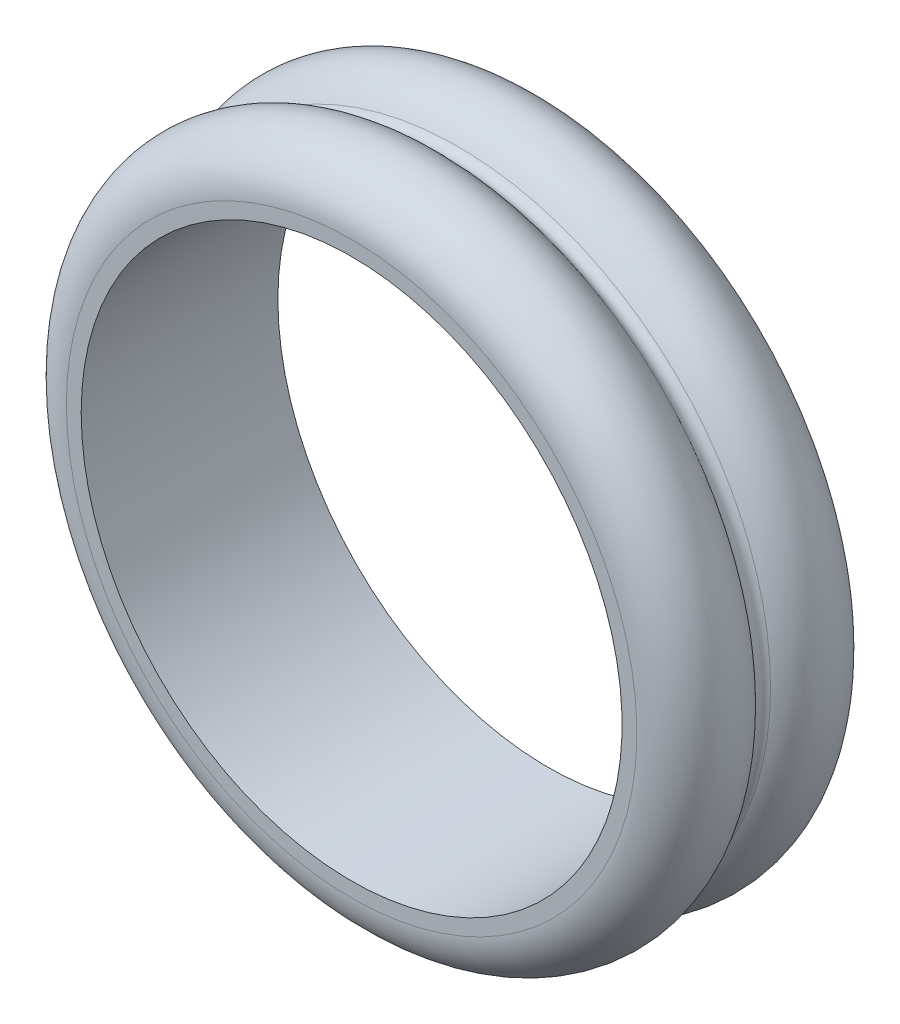
SolidWorks part; units mm, degrees
material "尼龙 6/10"
ref_plane "前视基准面" through (0, 0, 0) normal (0, 0, 1) x (1, 0, 0)
ref_plane "上视基准面" through (0, 0, 0) normal (0, 1, 0) x (1, 0, 0)
ref_plane "右视基准面" through (0, 0, 0) normal (1, 0, 0) x (0, 0, -1)
sketch "草图1" plane through (0, 0, 0) normal (0, 1, 0) x (1, 0, 0)
  line L0 (25, 10) -> (25, -10)
  line L1 (0, 146.934) -> (0, -105.6267) construction
  line L2 (25, 10) -> (29, 10)
  line L3 (25, -10) -> (29, -10)
  line L4 (-236.5493, 0) -> (326.6118, 0) construction
  arc A0 (31.7639, 0.8333) -> (29, 10) centre (29, 5) ccw
  arc A1 (31.7639, 0.8333) -> (31.7639, -0.8333) centre (32.3166, 0) ccw
  arc A2 (29, -10) -> (31.7639, -0.8333) centre (29, -5) ccw
  point P15 (29, 0)
  dimension "D4" = 1
  dimension "D1" = 20
  dimension "D2" = 25
  dimension "D3" = 29
revolve "旋转1" add sketch "草图1" angle 360 about L1
ref_plane "基准面1" through (0, 0, 6) normal (0, 0, 1) x (1, 0, 0)
sketch "草图2" plane through (0, 0, 6) normal (0, 0, 1) x (1, 0, 0)
  line L0 (0, 38.7462) -> (0, -39.0495) construction
  circle A0 centre (0, 0) radius 21.5 construction
  circle A1 centre (0, 21.5) radius 5
  dimension "D1" = 43
  dimension "D2" = 10
extrude "凸台-拉伸1" add sketch "草图2" against normal blind 10
pattern_circular "阵列(圆周)1" count 6 over 360 about axis through (0, 0, 0) along (0, 0, 1) of "凸台-拉伸1"
sketch "草图3" plane through (0, 0, 6) normal (0, 0, 1) x (1, 0, 0)
  line L0 (-8.0829, 0) -> (-10.8744, -4.8349)
  line L1 (0, 14) -> (-12.1244, 7) construction
  line L2 (-12.1244, 7) -> (-12.1244, -7) construction
  line L3 (-12.1244, -7) -> (0, -14) construction
  line L4 (0, -14) -> (12.1244, -7) construction
  line L5 (12.1244, -7) -> (12.1244, 7) construction
  line L6 (12.1244, 7) -> (0, 14) construction
  line L7 (-9.6244, -7) -> (-4.0415, -7)
  line L8 (10.8744, -4.8349) -> (8.0829, 0)
  line L9 (9.6244, 7) -> (4.0415, 7)
  line L10 (-10.8744, 4.8349) -> (-8.0829, 0)
  line L11 (-4.0415, -7) -> (-1.25, -11.8349)
  line L12 (0, 43.2923) -> (0, -38.3052) construction
  line L13 (-1.25, 16.6588) -> (-1.25, 11.8349)
  line L14 (1.25, 11.8349) -> (1.25, 16.6588)
  line L15 (10.8744, 4.8349) -> (15.0519, 7.2469)
  line L16 (13.8019, 9.4119) -> (9.6244, 7)
  line L17 (9.6244, -7) -> (13.8019, -9.4119)
  line L18 (15.0519, -7.2469) -> (10.8744, -4.8349)
  line L19 (-1.25, -11.8349) -> (-1.25, -16.6588)
  line L20 (1.25, -16.6588) -> (1.25, -11.8349)
  line L21 (-10.8744, -4.8349) -> (-15.0519, -7.2469)
  line L22 (-13.8019, -9.4119) -> (-9.6244, -7)
  line L23 (-9.6244, 7) -> (-13.8019, 9.4119)
  line L24 (-15.0519, 7.2469) -> (-10.8744, 4.8349)
  line L25 (-1.25, 11.8349) -> (-4.0415, 7)
  line L26 (1.25, -11.8349) -> (4.0415, -7)
  line L27 (4.0415, -7) -> (9.6244, -7)
  line L28 (-4.0415, 7) -> (-9.6244, 7)
  line L29 (4.0415, 7) -> (1.25, 11.8349)
  line L30 (8.0829, 0) -> (10.8744, 4.8349)
  circle A0 centre (0, 0) radius 12.1244 construction
  arc A1 (-3.839, 24.7035) -> (3.839, 24.7035) centre (0, 21.5) ccw construction
  arc A2 (-1.25, 16.6588) -> (1.25, 16.6588) centre (0, 21.5) ccw
  arc A3 (-23.3133, 9.0271) -> (-19.4744, 15.6764) centre (-18.6195, 10.75) ccw construction
  arc A4 (-19.4744, -15.6764) -> (-23.3133, -9.0271) centre (-18.6195, -10.75) ccw construction
  arc A5 (3.839, -24.7035) -> (-3.839, -24.7035) centre (0, -21.5) ccw construction
  arc A6 (23.3133, -9.0271) -> (19.4744, -15.6764) centre (18.6195, -10.75) ccw construction
  arc A7 (19.4744, 15.6764) -> (23.3133, 9.0271) centre (18.6195, 10.75) ccw construction
  arc A8 (-15.0519, 7.2469) -> (-13.8019, 9.4119) centre (-18.6195, 10.75) ccw
  arc A9 (-13.8019, -9.4119) -> (-15.0519, -7.2469) centre (-18.6195, -10.75) ccw
  arc A10 (1.25, -16.6588) -> (-1.25, -16.6588) centre (0, -21.5) ccw
  arc A11 (15.0519, -7.2469) -> (13.8019, -9.4119) centre (18.6195, -10.75) ccw
  arc A12 (13.8019, 9.4119) -> (15.0519, 7.2469) centre (18.6195, 10.75) ccw
  point P41 (0, 0)
  dimension "D1" = 28
  dimension "D2" = 2.5
  dimension "D3" = 6
extrude "凸台-拉伸2" add sketch "草图3" against normal blind 7
sketch "草图4" plane through (0, 0, -1) normal (0, 0, -1) x (-1, 0, 0)
  line L0 (0, 15.11) -> (0, -12.4392) construction
  circle A0 centre (0, 0) radius 8.5 construction
  circle A1 centre (0, 8.5) radius 1.4
  dimension "D1" = 17
  dimension "D2" = 2.8
extrude "切除-拉伸1" cut sketch "草图4" against normal through all
pattern_circular "阵列(圆周)2" count 6 over 360 about axis through (0, 0, 0) along (0, 0, 1) of "切除-拉伸1"
sketch "草图5" plane through (0, 0, -1) normal (0, 0, -1) x (-1, 0, 0)
  circle A0 centre (0, 0) radius 5.5
  dimension "D1" = 11
extrude "凸台-拉伸3" add sketch "草图5" along normal blind 5
sketch "草图7" plane through (0, 0, 6) normal (0, 0, 1) x (1, 0, 0)
  circle A0 centre (0, 0) radius 7
  dimension "D1" = 14
extrude "切除-拉伸3" cut sketch "草图7" against normal blind 1.5 draft 40
sketch "草图8" plane through (0, 0, 4.5) normal (0, 0, 1) x (1, 0, 0)
  circle A0 centre (0, 0) radius 1.5
  dimension "D1" = 3
extrude "切除-拉伸4" cut sketch "草图8" against normal through all
sketch "草图9" plane through (0, 0, -6) normal (0, 0, -1) x (-1, 0, 0)
  line L1 (3.5, 0) -> (1.75, 3.0311)
  line L2 (3.5, 0) -> (1.75, -3.0311)
  line L3 (1.75, -3.0311) -> (-1.75, -3.0311)
  line L4 (-3.5, 0) -> (-1.75, -3.0311)
  line L5 (1.75, 3.0311) -> (-1.75, 3.0311)
  line L6 (-3.5, 0) -> (-1.75, 3.0311)
sketch "草图10" plane through (0, 0, 6) normal (0, 0, 1) x (1, 0, 0)
  circle A0 centre (0, 21.5) radius 1.25
  dimension "D1" = 2.5
extrude "切除-拉伸6" cut sketch "草图10" against normal through all
pattern_circular "阵列(圆周)3" count 6 over 360 about axis through (0, 0, 0) along (0, 0, 1) of "切除-拉伸6"
sketch "草图11" plane through (0, 0, 6) normal (0, 0, 1) x (1, 0, 0)
  circle A0 centre (0, 21.5) radius 2.5
  dimension "D1" = 5
extrude "切除-拉伸7" cut sketch "草图11" against normal through all
pattern_circular "阵列(圆周)4" count 2 over 360 about axis through (0, 0, 0) along (0, 0, 1) of "切除-拉伸7"
sketch "草图12" plane through (0, 0, 6) normal (0, 0, 1) x (1, 0, 0)
  line L1 (20.0629, 8.25) -> (21.5063, 10.75)
  line L2 (21.5063, 10.75) -> (20.0629, 13.25)
  line L3 (20.0629, 13.25) -> (17.1762, 13.25)
  line L4 (17.1762, 13.25) -> (15.7328, 10.75)
  line L5 (15.7328, 10.75) -> (17.1762, 8.25)
  line L6 (17.1762, 8.25) -> (20.0629, 8.25)
  circle A0 centre (18.6195, 10.75) radius 2.5 construction
  dimension "D1" = 5
extrude "切除-拉伸8" cut sketch "草图12" against normal blind 8
pattern_circular "阵列(圆周)5" count 6 over 360 about axis through (0, 0, 0) along (0, 0, 1) skipping 2, 5 of "切除-拉伸8"
extrude "切除-拉伸9" cut sketch "草图9" against normal blind 8
sketch "草图14" plane through (0, 0, -10) normal (0, 0, -1) x (-1, 0, 0)
  circle A0 centre (0, 0) radius 27.5
  dimension "D1" = 55
extrude "切除-拉伸11" cut sketch "草图14" against normal blind 55
